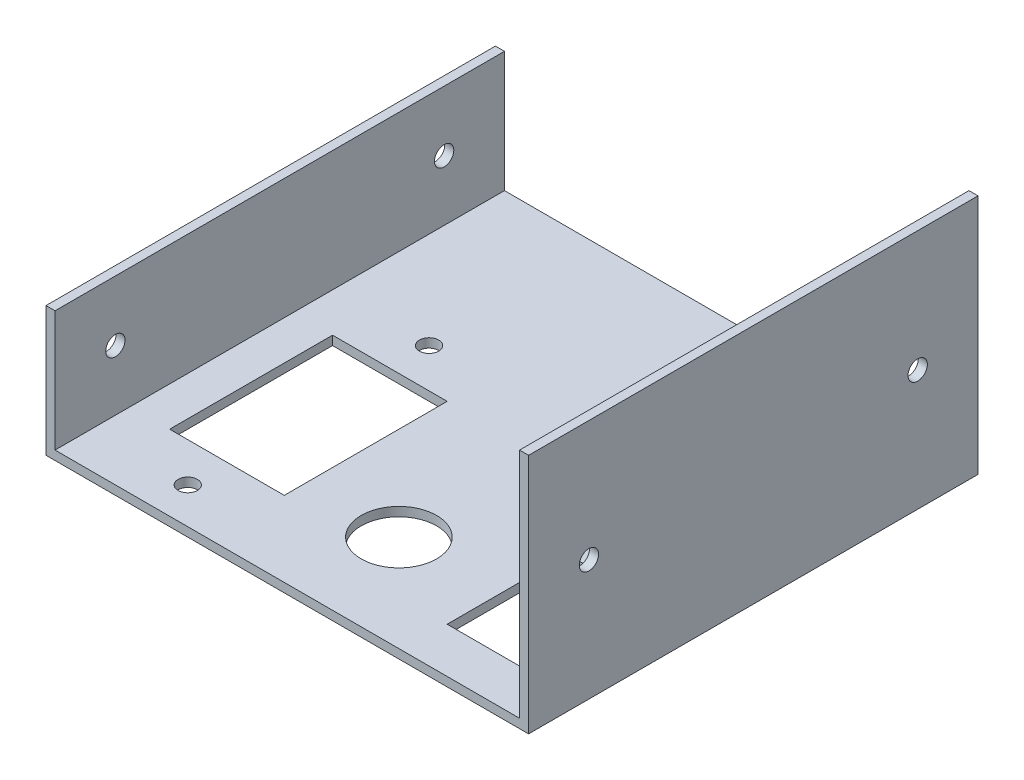
SolidWorks part; units mm, degrees
ref_plane "Front Plane" through (0, 0, 0) normal (0, 0, 1) x (1, 0, 0)
ref_plane "Top Plane" through (0, 0, 0) normal (0, 1, 0) x (1, 0, 0)
ref_plane "Right Plane" through (0, 0, 0) normal (1, 0, 0) x (0, 0, -1)
sketch "Sketch1" plane through (0, 0, 0) normal (0, 1, 0) x (1, 0, 0)
  line L1 (-40, -37.25) -> (40, -37.25)
  line L2 (-40, -37.25) -> (-40, 37.25)
  line L3 (-40, 37.25) -> (40, 37.25)
  line L4 (40, -37.25) -> (40, 37.25)
  line L5 (-40, -37.25) -> (40, 37.25) construction
  line L6 (-40, 37.25) -> (40, -37.25) construction
  point P0 (0, 0)
  dimension "D1" = 74.5
  dimension "D2" = 80
extrude "Boss-Extrude1" add sketch "Sketch1" along normal blind 1.5
sketch "Sketch2" plane through (0, 1.5, 0) normal (0, 1, 0) x (1, 0, 0)
  line L0 (-40, -37.25) -> (40, -37.25) construction
  line L1 (-40, 37.25) -> (-38.5, 37.25)
  line L2 (-40, 37.25) -> (-40, -37.25)
  line L3 (-40, -37.25) -> (-38.5, -37.25)
  line L4 (-38.5, 37.25) -> (-38.5, -37.25)
  dimension "D1" = 1.5
extrude "Boss-Extrude2" add sketch "Sketch2" along normal blind 20
sketch "Sketch3" plane through (0, 1.5, 0) normal (0, 1, 0) x (1, 0, 0)
  line L0 (-38.5, -37.25) -> (40, -37.25) construction
  line L1 (40, 37.25) -> (38.5, 37.25)
  line L2 (40, 37.25) -> (40, -37.25)
  line L3 (40, -37.25) -> (38.5, -37.25)
  line L4 (38.5, 37.25) -> (38.5, -37.25)
  dimension "D1" = 1.5
extrude "Boss-Extrude3" add sketch "Sketch3" along normal blind 38.5
sketch "Sketch4" plane through (0, 1.5, 0) normal (0, 1, 0) x (1, 0, 0)
  line L1 (-32, 2.25) -> (-13, 2.25)
  line L2 (-32, 2.25) -> (-32, -24.75)
  line L3 (-32, -24.75) -> (-13, -24.75)
  line L4 (-13, 2.25) -> (-13, -24.75)
  line L5 (-32, -11.25) -> (-13, -11.25) construction
  line L6 (-22.5, 2.25) -> (-22.5, -24.75) construction
  line L8 (-38.5, -37.25) -> (-38.5, 37.25) construction
  line L9 (-38.5, -37.25) -> (38.5, -37.25) construction
  line L10 (19, -9.75) -> (31, -9.75)
  line L11 (19, -9.75) -> (19, -29.75)
  line L12 (19, -29.75) -> (31, -29.75)
  line L13 (31, -9.75) -> (31, -29.75)
  circle A0 centre (-22.5, 8.75) radius 1.6
  circle A1 centre (-22.5, -31.25) radius 1.6
  circle A2 centre (2.5, -21.25) radius 6.25
  dimension "D5" = 3.2
  dimension "D6" = 3.2
  dimension "D9" = 12.5
  dimension "D1" = 19
  dimension "D2" = 27
  dimension "D3" = 26
  dimension "D4" = 16
  dimension "D7" = 20
  dimension "D8" = 20
  dimension "D10" = 25
  dimension "D11" = 16
  dimension "D12" = 12
  dimension "D13" = 20
  dimension "D14" = 32
  dimension "D15" = 7.5
extrude "Cut-Extrude1" cut sketch "Sketch4" against normal blind 40
sketch "Sketch5" plane through (-40, 0, 0) normal (-1, 0, 0) x (0, 0, 1)
  line L0 (-37.25, 21.5) -> (-37.25, 0) construction
  line L1 (37.25, 21.5) -> (37.25, 0) construction
  line L2 (-37.25, 21.5) -> (37.25, 21.5) construction
  circle A0 centre (27.25, 11.5) radius 1.6
  circle A1 centre (-27.25, 11.5) radius 1.6
  dimension "D1" = 3.2
  dimension "D2" = 3.2
  dimension "D3" = 10
  dimension "D4" = 10
  dimension "D5" = 10
  dimension "D6" = 10
extrude "Cut-Extrude2" cut sketch "Sketch5" against normal blind 40
sketch "Sketch6" plane through (40, 0, 0) normal (1, 0, 0) x (0, 0, -1)
  line L0 (-37.25, 40) -> (-37.25, 0) construction
  line L1 (37.25, 40) -> (37.25, 0) construction
  line L2 (-37.25, 40) -> (37.25, 40) construction
  circle A0 centre (-27.25, 20) radius 1.6
  circle A1 centre (27.25, 20) radius 1.6
  dimension "D1" = 3.2
  dimension "D2" = 3.2
  dimension "D3" = 10
  dimension "D4" = 10
  dimension "D5" = 20
  dimension "D6" = 20
extrude "Cut-Extrude3" cut sketch "Sketch6" against normal blind 40
sketch "Sketch8" plane through (0, 1.5, 0) normal (0, 1, 0) x (1, 0, 0)
  circle A0 centre (-35, 25.25) radius 1.6
  dimension "D1" = 3.2
